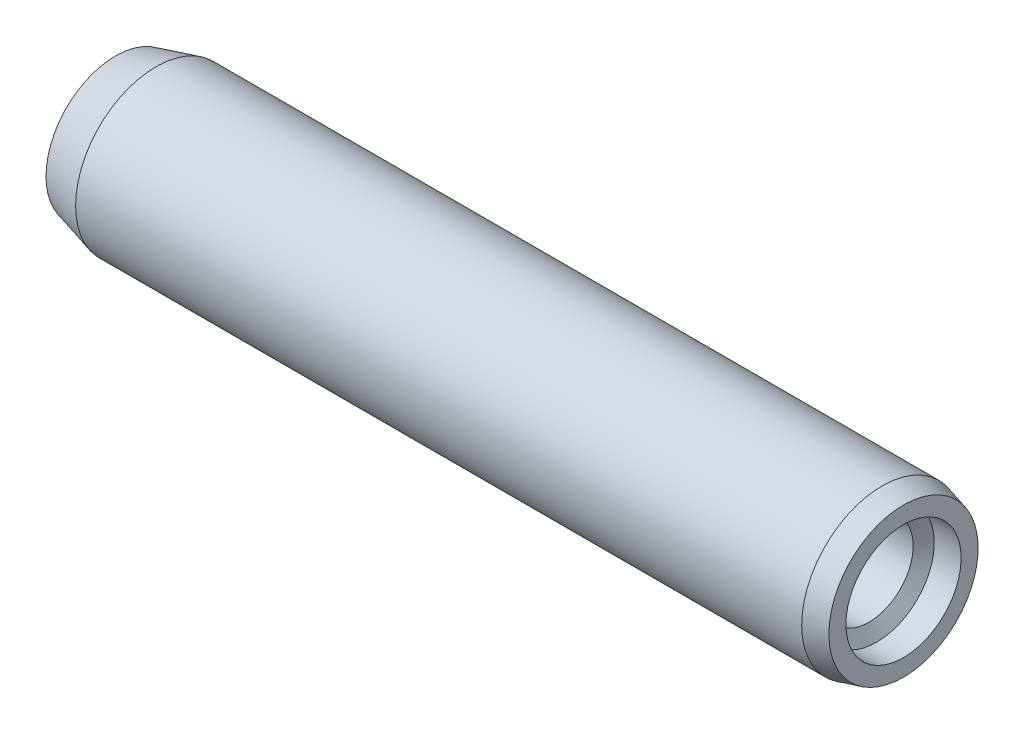
SolidWorks part; units mm, degrees
revolve "Base-Revolve" add sketch "Sketch1" angle 360 about L0
sketch "Sketch1" plane through (0, 0, 0) normal (0, 0, 1) x (1, 0, 0)
  line L0 (-10, 0) -> (106, 0) construction
  line L1 (0, 0) -> (0, 2.4373)
  line L2 (2.1, 3) -> (29.2, 3)
  line L3 (30, 2.7856) -> (30, 2.15)
  line L4 (19.0086, 0) -> (0, 0)
  line L5 (2.1, 3) -> (0, 2.4373)
  line L6 (30, 2.7856) -> (29.2, 3)
  line L7 (19.0086, 0) -> (20, 1.65)
  line L8 (20, 1.65) -> (28.7113, 1.65)
  line L9 (28.7113, 1.65) -> (29, 2.15)
  line L10 (28.7113, -1.65) -> (29, -2.15) construction
  line L11 (29, 2.15) -> (30, 2.15)
  line L12 (19.0086, 0) -> (20, -1.65) construction
  dimension "D1" = 15
  dimension "Length" = 30
  dimension "D2" = 75
  dimension "ChamferLengthA" = 0.8
  dimension "D3" = 120
  dimension "Diameter" = 6
  dimension "CboreDia" = 4.3
  dimension "D4" = 118
  dimension "CboreDepth" = 1
  dimension "TapDrillDepth" = 10
  dimension "TapDrillDia" = 3.3
  dimension "ChamferLengthC" = 2.1
cosmetic thread "Cosmetic Thread1" [suppressed]
ref_plane "Plane1" through (0, 0, 0) normal (0, 0, 1) x (1, 0, 0)
ref_plane "Plane2" through (0, 0, 0) normal (0, 1, 0) x (1, 0, 0)
ref_plane "Plane3" through (0, 0, 0) normal (1, 0, 0) x (0, 0, -1)
sketch "Sketch2" plane through (0, 0, 0) normal (0, 0, 1) x (1, 0, 0)
  line L0 (0, 0) -> (26, 0) construction
  line L1 (-10, 0) -> (106, 0) construction
  line L2 (0, 2.4373) -> (0, -2.4373) construction
  line L3 (0.5904, 2.5955) -> (0.5904, 8)
  line L5 (0.5904, 8) -> (-5, 8)
  line L6 (-5, 8) -> (-5, 0)
  line L7 (-5, 0) -> (0, 0)
  line L8 (2.1, 3) -> (0, 2.4373) construction
  line L9 (29.2, 3) -> (2.1, 3) construction
  arc A0 (0.5904, 2.5955) -> (0, 0) centre (6, 0) ccw
  dimension "D1" = 6
  dimension "D2" = 5
  dimension "D3" = 5
revolve "TypeA" cut sketch "Sketch2" angle 360 about L0
equation "\"D1@Sketch2\" = \"Diameter@Sketch1\""
